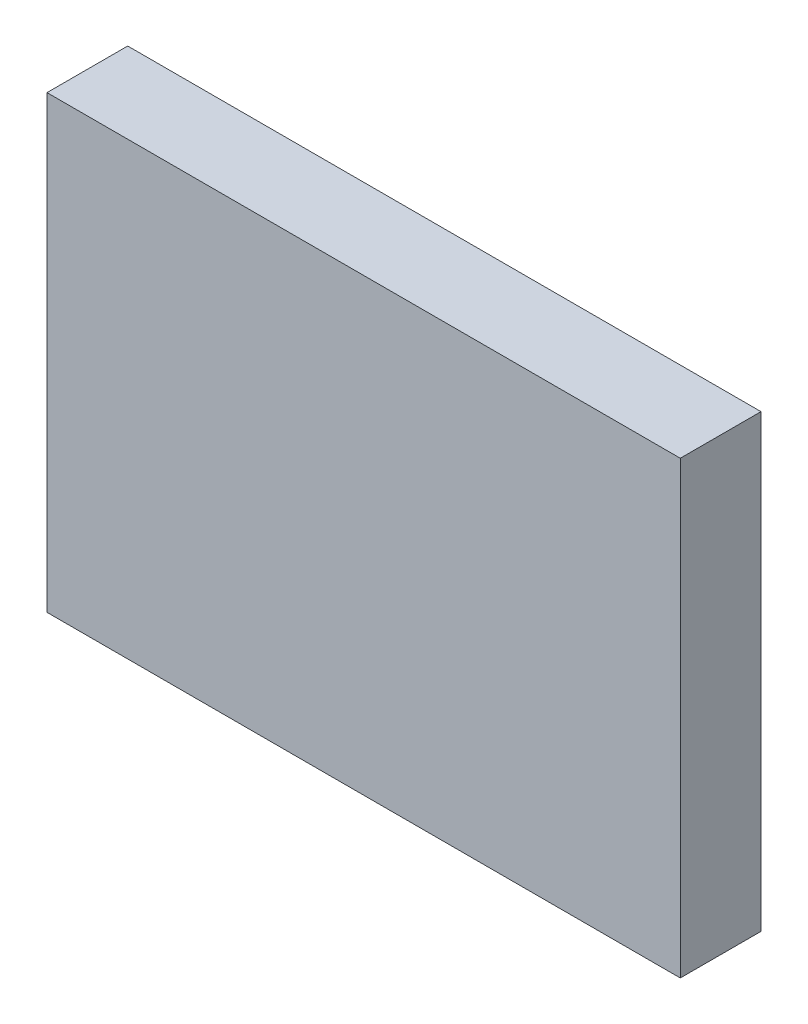
SolidWorks part; units mm, degrees
material "Balsa"
ref_plane "Plano frontal" through (0, 0, 0) normal (0, 0, 1) x (1, 0, 0)
ref_plane "Plano superior" through (0, 0, 0) normal (0, 1, 0) x (1, 0, 0)
ref_plane "Plano direito" through (0, 0, 0) normal (1, 0, 0) x (0, 0, -1)
sketch "Esboço1" plane through (0, 0, 0) normal (0, 0, 1) x (1, 0, 0)
  line L1 (0, 0) -> (-20.4, 0)
  line L2 (0, 0) -> (0, 14.5)
  line L3 (0, 14.5) -> (-20.4, 14.5)
  line L4 (-20.4, 0) -> (-20.4, 14.5)
  dimension "D1" = 14.5
  dimension "D2" = 20.4
extrude "Ressalto-extrusão1" add sketch "Esboço1" along normal blind 2.6
